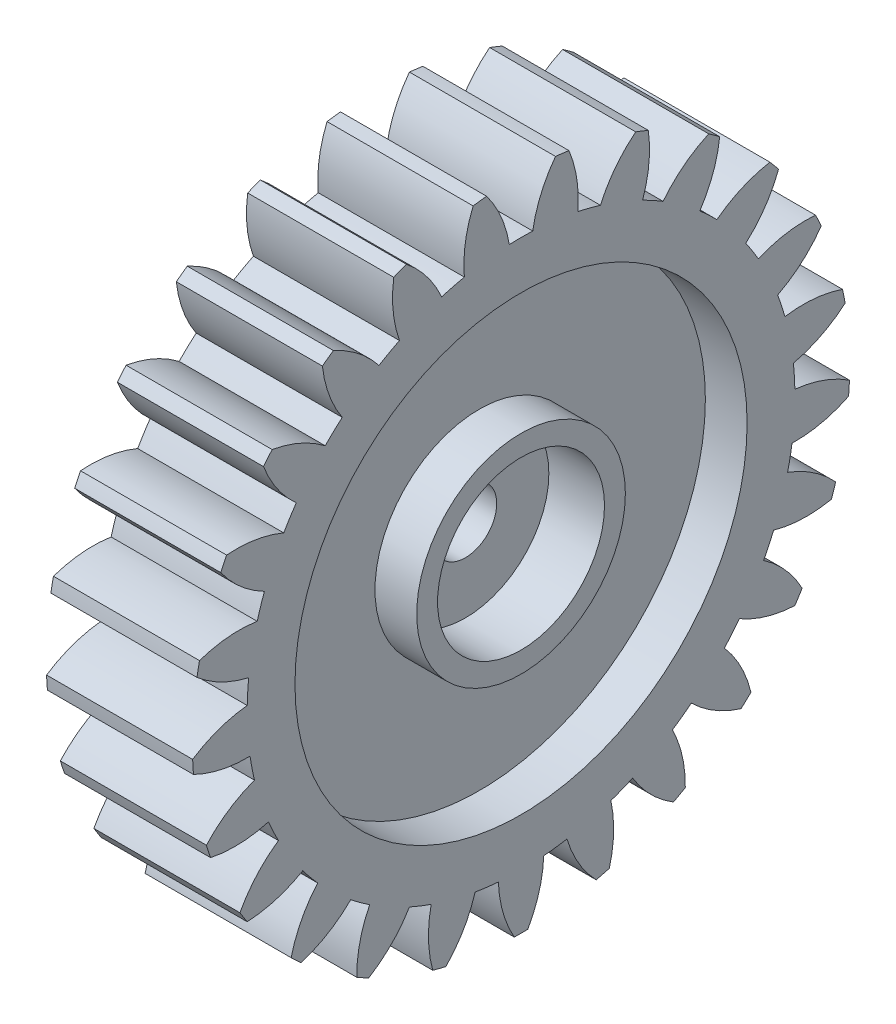
SolidWorks part; units mm, degrees
ref_plane "Plane1" through (0, 0, 0) normal (0, 0, 1) x (1, 0, 0)
ref_plane "Plane2" through (0, 0, 0) normal (0, 1, 0) x (1, 0, 0)
ref_plane "Plane3" through (0, 0, 0) normal (1, 0, 0) x (0, 0, -1)
other "Configuration Table"
sketch "HoldingSke" plane through (0, 0, 0) normal (0, 1, 0) x (1, 0, 0)
  line L0 (0, 0) -> (1.2947, -0.6037)
  line L1 (-15, 0) -> (100, 0) construction
  line L2 (0, 0) -> (-2.1039, 2.3779)
  line L3 (0, 0) -> (-11.863, 4.5341)
  line L4 (0, 0) -> (7.8269, 3.6497)
  line L5 (0, 0) -> (-46.8476, -17.4728)
  line L6 (0, 0) -> (-1.6579, -1.1186)
  line L7 (-2.1039, 2.3779) -> (8.6586, 51.2059)
  line L8 (-76.2, 54.61) -> (-75.3, 54.61)
  line L9 (-71.009, 38.7566) -> (-53.1078, 45.2721)
  line L10 (-76.2, 71.12) -> (104.1128, 71.12)
  line L11 (0, 0) -> (-2, 0)
  line L12 (-76.2, 101.6) -> (-76.173, 101.6)
  line L13 (24.9733, 27.94) -> (52.9518, 28.4284)
  line L14 (24.9733, 27.94) -> (24.9743, 27.94)
  line L15 (24.9733, 27.94) -> (100.4006, 29.5858)
  line L16 (-63.627, -0.7) -> (-12.827, -0.7)
  circle A0 centre (0, 0) radius 2.5
  circle A1 centre (0, 0) radius 7.874
  circle A2 centre (0, 0) radius 37.5
  circle A3 centre (0, 0) radius 2.5
  dimension "MHD" = 15.748
  dimension "Hub_dia" = 75
  dimension "Bore" = 5
  dimension "MBD" = 5
  dimension "Num_teeth" = 25
  dimension "Pitch" = 1.4286
  dimension "Overall_len" = 50
  dimension "Show_teeth" = 25
  dimension "Thickness" = 2
  dimension "OAL" = 50.0001
  dimension "T_dim" = 0.9
  dimension "Ap" = 20
  dimension "H" = 19.05
  dimension "Pitch_radius" = 180.3128
  dimension "Width" = 2
  dimension "Backlash" = 0.027
  dimension "Addendum_fac" = 1
  dimension "Dedendum_fac" = 1.25
  dimension "Clearance_fac" = 0.25
  dimension "Dedendum_add" = 0.001
  dimension "Module" = 0.7
sketch "BasProSke" plane through (0, 0, 0) normal (0, 1, 0) x (1, 0, 0)
  line L0 (-10, 0) -> (60, 0) construction
  line L1 (0, 0) -> (0, 9.45)
  line L2 (0, 0) -> (4.2, 0)
  line L3 (4.2, 0) -> (4.2, 9.45)
  line L4 (4.2, 9.45) -> (0, 9.45)
  dimension "Thickness" = 4.2
  dimension "Diameter" = 18.9
revolve "Base-Revolve" add sketch "BasProSke" angle 360 about L0
sketch "TooCutSke" plane through (0, 0, 0) normal (1, 0, 0) x (0, 0, -1)
  line L1 (0, 0) -> (0, 107) construction
  line L2 (0, 0) -> (-0.5967, 8.7296) construction
  line L3 (0, 0) -> (-2.1897, 17.3334) construction
  line L4 (-0.5967, 8.7296) -> (-1.0949, 8.6667) construction
  arc A0 (0.3366, 7.8668) -> (-0.3366, 7.8668) centre (0, 0) ccw
  arc A1 (1.0087, 9.4216) -> (-1.0087, 9.4216) centre (0, 0) ccw
  circle A2 centre (0, 0) radius 8.75 construction
  circle A3 centre (0, 0) radius 8.2223 construction
  arc A4 (-0.3366, 7.8668) -> (-1.0087, 9.4216) centre (-3.7899, 7.2968) ccw
  arc A5 (1.0087, 9.4216) -> (0.3366, 7.8668) centre (3.7899, 7.2968) ccw
  dimension "Root_dia" = 15.748
  dimension "Overcut_dia" = 18.9508
  dimension "Pitch_dia" = 17.5
  dimension "Base_dia" = 16.4446
  dimension "Flank_rad" = 3.5
  dimension "Half_ang" = 7.2
  dimension "Half_CT" = 0.5022
extrude "ToothCut" cut sketch "TooCutSke" along normal through all
fillet "Breaks" [suppressed] radius 0.014
fillet "RootFillets" [suppressed] radius 0.176
pattern_circular "TeethCuts" count 25 every 14.4 about axis through (-10, 0, 0) along (1, 0, 0) of "ToothCut", "RootFillets", "Breaks"
sketch "HubNeaOneSke" plane through (0, 0, 0) normal (-1, 0, 0) x (0, 0, 1)
  circle A0 centre (0, 0) radius 7.874
  dimension "Diameter" = 15.748
extrude "HubNearOne" [suppressed] add sketch "HubNeaOneSke" along normal blind 45.8001
sketch "HubNeaBotSke" plane through (0, 0, 0) normal (-1, 0, 0) x (0, 0, 1)
  circle A0 centre (0, 0) radius 7.874
  dimension "Diameter" = 15.748
extrude "HubNearBoth" [suppressed] add sketch "HubNeaBotSke" along normal blind 22.9
ref_plane "FarPln" through (4.2, 0, 0) normal (1, 0, 0) x (0, 0, -1)
sketch "HubFarSke" plane through (4.2, 0, 0) normal (1, 0, 0) x (0, 0, -1)
  circle A0 centre (0, 0) radius 7.874
  dimension "Diameter" = 15.748
extrude "HubFar" [suppressed] add sketch "HubFarSke" along normal blind 22.9
sketch "BorSke" plane through (0, 0, 0) normal (1, 0, 0) x (0, 0, -1)
  circle A0 centre (0, 0) radius 2.5
  dimension "Diameter" = 5
extrude "Bore" [suppressed] cut sketch "BorSke" along normal mid plane 100.0001
sketch "KeySke" plane through (0, 0, 0) normal (1, 0, 0) x (0, 0, -1)
  line L0 (-1, 0) -> (-1, 3.4)
  line L1 (-1, 3.4) -> (1, 3.4)
  line L2 (1, 3.4) -> (1, 0)
  line L3 (0, 0) -> (0, 34) construction
  line L4 (-1, 0) -> (1, 0)
  dimension "Width" = 2
  dimension "Offset" = 3.4
extrude "Keyway" [suppressed] cut sketch "KeySke" along normal mid plane 100.0001
pattern_circular "Keyway2" [suppressed] count 2 every 90 about axis through (-10, 0, 0) along (1, 0, 0)
sketch "Sketch4" plane through (4.2, 0, 0) normal (1, 0, 0) x (0, 0, -1)
  circle A0 centre (0, 0) radius 9.45 construction
sketch "Sketch7" plane through (4.2, 0, 0) normal (1, 0, 0) x (0, 0, -1)
  circle A0 centre (0, 0) radius 2.4
  dimension "D1" = 4.8
extrude "Cut-Extrude2" cut sketch "Sketch7" against normal blind 1.6
sketch "Sketch13" plane through (4.2, 0, 0) normal (1, 0, 0) x (0, 0, -1)
  circle A0 centre (0, 0) radius 3
  circle A1 centre (0, 0) radius 6.5
  dimension "D1" = 6
  dimension "D2" = 13
extrude "Cut-Extrude3" cut sketch "Sketch13" against normal blind 1.2
sketch "Sketch15" plane through (0, 0, 0) normal (-1, 0, 0) x (0, 0, 1)
  circle A0 centre (0, 0) radius 3
  circle A1 centre (0, 0) radius 6.5
  dimension "D1" = 6
  dimension "D2" = 13
extrude "Cut-Extrude4" cut sketch "Sketch15" against normal blind 1.2
sketch "Sketch17" plane through (0, 0, 0) normal (-1, 0, 0) x (0, 0, 1)
  circle A0 centre (0, 0) radius 2.4
  dimension "D1" = 4.8
extrude "Cut-Extrude5" cut sketch "Sketch17" against normal blind 1.6
sketch "Sketch18" plane through (2.6, 0, 0) normal (1, 0, 0) x (0, 0, -1)
  circle A0 centre (0, 0) radius 0.9
  dimension "D1" = 1.8
extrude "Cut-Extrude6" cut sketch "Sketch18" against normal blind 1.6
equation "' \"Module@HoldingSke\" = 6.35"
equation "' \"Num_teeth@HoldingSke\" = 12"
equation "' \"Ap@HoldingSke\" =  20"
equation "' \"Ap@HoldingSke\" = 20"
equation "' \"Width@HoldingSke\" = 0.5 * 25.4"
equation "' \"Hub_dia@HoldingSke\"= 1 * 25.4"
equation "' \"Hub_dia@HoldingSke\" = 1 * 25.4"
equation "' \"Overall_len@HoldingSke\" = 1.0 * 25.4"
equation "' \"Bore@HoldingSke\" = 0.75 * 25.4"
equation "' \"T_dim@HoldingSke\" = 0.1 * 25.4"
equation "' \"Width@KeySke\" = 0.25 * 25.4"
equation "' \"Show_teeth@HoldingSke\" = 13"
equation "' \"Backlash@HoldingSke\" = 0.009 * 25.4"
equation "' \"Addendum_fac@HoldingSke\" = 1.0"
equation "' \"Dedendum_fac@HoldingSke\" = 1.25"
equation "' \"Dedendum_add@HoldingSke\" = 0.00005 * 25.4"
equation "' \"Clearance_fac@HoldingSke\" = 0.25"
equation "\"Pitch@HoldingSke\" = 1 / \"Module@HoldingSke\""
equation "\"Overcut_dia@TooCutSke\" = (\"Num_teeth@HoldingSke\" + 2 * \"Addendum_fac@HoldingSke\") / \"Pitch@HoldingSke\" + 0.002 * 25.4"
equation "\"Pitch_dia@TooCutSke\" = \"Num_teeth@HoldingSke\" / \"Pitch@HoldingSke\""
equation "\"Base_dia@TooCutSke\" = \"Num_teeth@HoldingSke\" / \"Pitch@HoldingSke\" * cos((\"Ap@HoldingSke\"  * 3.14159265 / 180))"
equation "\"Root_dia@TooCutSke\" = (\"Num_teeth@HoldingSke\" + 2) / \"Pitch@HoldingSke\" - 2 * (\"Addendum_fac@HoldingSke\" + \"Dedendum_fac@HoldingSke\") / \"Pitch@HoldingSke\" - \"Dedendum_add@HoldingSke\" * 2"
equation "\"Half_ang@TooCutSke\" = 180 / \"Num_teeth@HoldingSke\""
equation "\"Half_CT@TooCutSke\" = \"Num_teeth@HoldingSke\" / \"Pitch@HoldingSke\" * sin((3.14159265 / 2 / \"Num_teeth@HoldingSke\")) / 2 - 7 * \"Backlash@HoldingSke\" / 4"
equation "\"Flank_rad@TooCutSke\" = \"Num_teeth@HoldingSke\" / \"Pitch@HoldingSke\" / 5"
equation "\"Radius@RootFillets\" = \"Clearance_fac@HoldingSke\" / \"Pitch@HoldingSke\" + \"Dedendum_add@HoldingSke\""
equation "\"Break_rad@Breaks\" = 0.02 / \"Pitch@HoldingSke\""
equation "\"Thickness@HoldingSke\" = \"Width@HoldingSke\""
equation "\"OAL@HoldingSke\" = \"Thickness@HoldingSke\""
equation "\"MHD@HoldingSke\" = (\"Num_teeth@HoldingSke\" + 2) / \"Pitch@HoldingSke\" - 2 * (\"Addendum_fac@HoldingSke\" + \"Dedendum_fac@HoldingSke\")  / \"Pitch@HoldingSke\" - \"Dedendum_add@HoldingSke\" * 2"
equation "\"MBD@HoldingSke\" = (\"Num_teeth@HoldingSke\" + 2) / \"Pitch@HoldingSke\" - 2 * (\"Addendum_fac@HoldingSke\" + \"Dedendum_fac@HoldingSke\")  / \"Pitch@HoldingSke\" - \"Dedendum_add@HoldingSke\" * 2 - 0.002 * 25.4"
equation "\"MHD@HoldingSke\" = ((sgn( \"MHD@HoldingSke\" - \"Hub_dia@HoldingSke\" )-1)*( \"MHD@HoldingSke\" - \"Hub_dia@HoldingSke\" ))/-2+ \"Hub_dia@HoldingSke\""
equation "\"MBD@HoldingSke\" = ((sgn( \"MBD@HoldingSke\" - \"Bore@HoldingSke\" )-1)*( \"MBD@HoldingSke\" - \"Bore@HoldingSke\" ))/-2+ \"Bore@HoldingSke\""
equation "\"OAL@HoldingSke\" = ((sgn( \"OAL@HoldingSke\" - \"Overall_len@HoldingSke\" )+1)*( \"OAL@HoldingSke\" - \"Overall_len@HoldingSke\" ))/2 + \"Overall_len@HoldingSke\" + 0.000002 * 25.4"
equation "\"Num_teeth@TeethCuts\" = int( \"Show_teeth@HoldingSke\" ) + 1"
equation "\"Num_teeth@TeethCuts\" = ((sgn( \"Num_teeth@TeethCuts\" - \"Num_teeth@HoldingSke\" )-1)*( \"Num_teeth@TeethCuts\" - \"Num_teeth@HoldingSke\" ))/-2+ \"Num_teeth@HoldingSke\""
equation "\"Num_teeth@TeethCuts\" = ((sgn( \"Num_teeth@TeethCuts\" - 2.0)+1)*( \"Num_teeth@TeethCuts\" - 2.0))/2 +2.0"
equation "\"Angle@TeethCuts\" = 360.0 / \"Num_teeth@HoldingSke\""
equation "\"Diameter@BasProSke\" = (\"Num_teeth@HoldingSke\" + 2 * \"Addendum_fac@HoldingSke\") / \"Pitch@HoldingSke\""
equation "' \"Fillet_rad@BasProSke\" =  \"Thickness@HoldingSke\" * 0.05"
equation "' \"Fillet_rad@BasProSke\" = \"Thickness@HoldingSke\" * 0.05"
equation "\"MHD@HoldingSke\" = ((sgn( \"MHD@HoldingSke\" - \"Root_dia@TooCutSke\" )-1)*( \"MHD@HoldingSke\" - \"Root_dia@TooCutSke\" ))/-2+ \"Root_dia@TooCutSke\""
equation "\"Diameter@HubNeaOneSke\" = \"MHD@HoldingSke\""
equation "\"Length@HubNearOne\" = \"OAL@HoldingSke\" - \"Thickness@BasProSke\""
equation "\"Diameter@HubNeaBotSke\" = \"MHD@HoldingSke\""
equation "\"Length@HubNearBoth\" = ( \"OAL@HoldingSke\" - \"Thickness@BasProSke\" ) / 2.0"
equation "\"Thickness@FarPln\" = \"Thickness@BasProSke\""
equation "\"Diameter@HubFarSke\" = \"MHD@HoldingSke\""
equation "\"Length@HubFar\" = ( \"OAL@HoldingSke\" - \"Thickness@BasProSke\" ) / 2.0"
equation "\"Diameter@BorSke\" = \"MBD@HoldingSke\""
equation "\"D1@Bore\" = \"OAL@HoldingSke\" * 2.0"
equation "\"D1@Keyway\" = \"OAL@HoldingSke\" * 2.0"
equation "\"Offset@KeySke\" = \"T_dim@HoldingSke\" + \"MBD@HoldingSke\" / 2.0"
